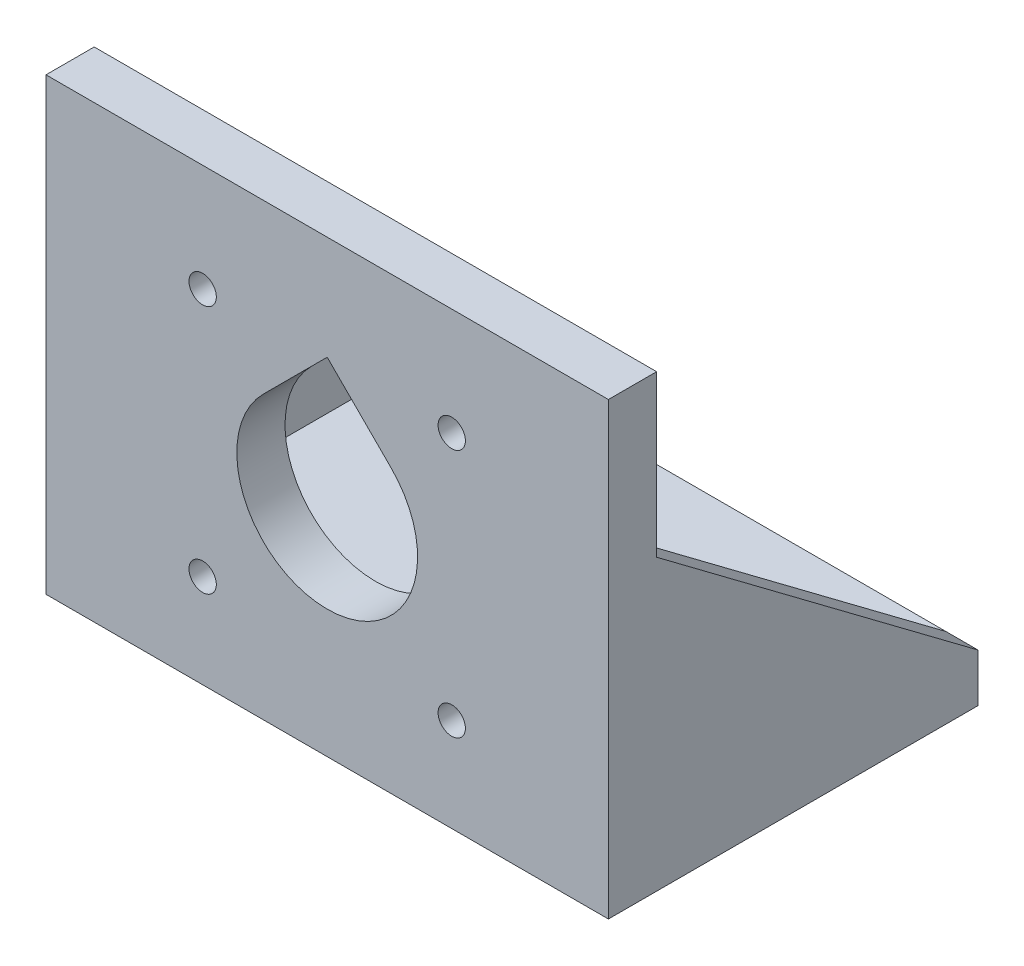
SolidWorks part; units mm, degrees
ref_plane "Спереди" through (0, 0, 0) normal (0, 0, 1) x (1, 0, 0)
ref_plane "Сверху" through (0, 0, 0) normal (0, 1, 0) x (1, 0, 0)
ref_plane "Справа" through (0, 0, 0) normal (1, 0, 0) x (0, 0, -1)
other "Configuration Table"
sketch "01_Пластина_эскиз" plane through (0, 0, 0) normal (0, 0, 1) x (1, 0, 0)
  line L1 (0, 0) -> (70, 0)
  line L2 (0, 0) -> (0, 56)
  line L3 (0, 56) -> (70, 56)
  line L4 (70, 0) -> (70, 56)
  dimension "D1" = 70
  dimension "D2" = 56
extrude "01_Передняя_пластина" add sketch "01_Пластина_эскиз" along normal blind 6
sketch "02_Полка_эскиз" plane through (0, 0, 0) normal (0, 1, 0) x (1, 0, 0)
  line L1 (0, 40) -> (70, 40)
  line L2 (0, 40) -> (0, -6)
  line L3 (0, -6) -> (70, -6)
  line L4 (70, 40) -> (70, -6)
  dimension "D1" = 70
  dimension "D2" = 46
  dimension "D3" = 6
  dimension "D4" = 6
extrude "02_Полка" add sketch "02_Полка_эскиз" along normal blind 6
sketch "03_Косынка_левая_эскиз" plane through (0, 0, 0) normal (1, 0, 0) x (0, 0, -1)
  line L0 (40, 6) -> (0, 6)
  line L1 (0, 6) -> (0, 36)
  line L2 (0, 36) -> (40, 6)
  dimension "D3" = 6
  dimension "D1" = 40
  dimension "D2" = 30
extrude "03_Косынка_левая" add sketch "03_Косынка_левая_эскиз" along normal blind 4
sketch "04_Косынка_правая_эскиз" plane through (0, 0, 0) normal (1, 0, 0) x (0, 0, -1)
  line L0 (40, 6) -> (0, 6)
  line L1 (0, 6) -> (0, 36)
  line L2 (0, 36) -> (40, 6)
  dimension "D3" = 6
  dimension "D1" = 40
  dimension "D2" = 30
extrude "04_Косынка_правая" add sketch "04_Косынка_правая_эскиз" along normal blind 4 from offset 66
sketch "05_Мотор_передний_фланец_эскиз" plane through (0, 0, 0) normal (0, 0, 1) x (1, 0, 0)
  line L0 (4, 6) -> (66, 6) construction
  circle A0 centre (35, 27.15) radius 11.25
  circle A1 centre (19.5, 11.65) radius 1.7
  circle A2 centre (19.5, 42.65) radius 1.7
  circle A3 centre (50.5, 11.65) radius 1.7
  circle A4 centre (50.5, 42.65) radius 1.7
  dimension "D1" = 3.4
  dimension "D2" = 3.4
  dimension "D3" = 3.4
  dimension "D4" = 3.4
  dimension "D5" = 22.5
  dimension "D6" = 15.5
  dimension "D7" = 31
  dimension "D8" = 15.5
  dimension "D9" = 31
  dimension "D10" = 35
  dimension "D11" = 21.15
extrude "05_Буртик_и_4_отверстия_М3" cut sketch "05_Мотор_передний_фланец_эскиз" against normal through all and the other way through all
sketch "06_Свод_45град_эскиз" plane through (0, 0, 0) normal (0, 0, 1) x (1, 0, 0)
  line L0 (27.045, 35.105) -> (42.955, 35.105)
  line L1 (42.955, 35.105) -> (35, 43.0599)
  line L2 (35, 43.0599) -> (27.045, 35.105)
  circle A0 centre (35, 27.15) radius 11.25 construction
  dimension "D1" = 7.955
  dimension "D2" = 15.9099
  dimension "D3" = 7.955
  dimension "D4" = 35
extrude "06_Свод_отверстия_для_печати" cut sketch "06_Свод_45град_эскиз" against normal through all and the other way through all
sketch "07_Крепление_полки_эскиз" plane through (0, 0, 0) normal (0, 1, 0) x (1, 0, 0)
  circle A0 centre (8.5, 12) radius 2.25
  circle A1 centre (8.5, 30) radius 2.25
  circle A2 centre (61.5, 12) radius 2.25
  circle A3 centre (61.5, 30) radius 2.25
  dimension "D1" = 4.5
  dimension "D2" = 4.5
  dimension "D3" = 4.5
  dimension "D4" = 4.5
  dimension "D5" = 53
  dimension "D6" = 18
  dimension "D7" = 8.5
  dimension "D8" = 12
extrude "07_4_отверстия_М4" cut sketch "07_Крепление_полки_эскиз" against normal through all and the other way through all
equation "\"Ширина\"= 70"
equation "\"Высота пластины\"= 56"
equation "\"Толщина стенок\"= 6"
equation "\"Длина полки\"= 40"
equation "\"Толщина косынки\"= 4"
equation "\"Высота косынки\"= 30"
equation "\"Высота оси\"= 30"
equation "\"Шаг М3 ПРЕДВ\"= 31"
equation "\"Отверстие буртика\"= 22.5"
equation "\"Отверстия М3\"= 3.4"
equation "\"Отверстия М4\"= 4.5"
equation "\"Отступ М4 сбоку\"= 8.5"
equation "\"Ближний ряд М4\"= 12"
equation "\"Отступ М4 сзади\"= 10"
equation "\"D1@01_Пластина_эскиз\" = \"Ширина\""
equation "\"D2@01_Пластина_эскиз\" = \"Высота пластины\""
equation "\"D1@01_Передняя_пластина\" = \"Толщина стенок\""
equation "\"D1@02_Полка_эскиз\" = \"Ширина\""
equation "\"D2@02_Полка_эскиз\" = \"Длина полки\" + \"Толщина стенок\""
equation "\"D1@02_Полка\" = \"Толщина стенок\""
equation "\"D1@03_Косынка_левая_эскиз\" = \"Длина полки\""
equation "\"D2@03_Косынка_левая_эскиз\" = \"Высота косынки\""
equation "\"D1@03_Косынка_левая\" = \"Толщина косынки\""
equation "\"D1@04_Косынка_правая_эскиз\" = \"Длина полки\""
equation "\"D2@04_Косынка_правая_эскиз\" = \"Высота косынки\""
equation "\"D1@04_Косынка_правая\" = \"Толщина косынки\""
equation "\"D19@04_Косынка_правая\" = \"Ширина\" - \"Толщина косынки\""
equation "\"D1@05_Мотор_передний_фланец_эскиз\" = \"Отверстия М3\""
equation "\"D2@05_Мотор_передний_фланец_эскиз\" = \"Отверстия М3\""
equation "\"D3@05_Мотор_передний_фланец_эскиз\" = \"Отверстия М3\""
equation "\"D4@05_Мотор_передний_фланец_эскиз\" = \"Отверстия М3\""
equation "\"D5@05_Мотор_передний_фланец_эскиз\" = \"Отверстие буртика\""
equation "\"D6@05_Мотор_передний_фланец_эскиз\" = \"Шаг М3 ПРЕДВ\" / 2"
equation "\"D7@05_Мотор_передний_фланец_эскиз\" = \"Шаг М3 ПРЕДВ\""
equation "\"D8@05_Мотор_передний_фланец_эскиз\" = \"Шаг М3 ПРЕДВ\" / 2"
equation "\"D9@05_Мотор_передний_фланец_эскиз\" = \"Шаг М3 ПРЕДВ\""
equation "\"D1@07_Крепление_полки_эскиз\" = \"Отверстия М4\""
equation "\"D2@07_Крепление_полки_эскиз\" = \"Отверстия М4\""
equation "\"D3@07_Крепление_полки_эскиз\" = \"Отверстия М4\""
equation "\"D4@07_Крепление_полки_эскиз\" = \"Отверстия М4\""
equation "\"D5@07_Крепление_полки_эскиз\" = \"Ширина\" - 2 * \"Отступ М4 сбоку\""
equation "\"D3@02_Полка_эскиз\" = \"Толщина стенок\""
equation "\"D3@03_Косынка_левая_эскиз\" = \"Толщина стенок\""
equation "\"D3@04_Косынка_правая_эскиз\" = \"Толщина стенок\""
equation "\"D10@05_Мотор_передний_фланец_эскиз\" = \"Ширина\" / 2"
equation "\"D1@06_Свод_45град_эскиз\" = \"Отверстие буртика\" / (2 * SQR(2))"
equation "\"D2@06_Свод_45град_эскиз\" = \"Отверстие буртика\" / SQR(2)"
equation "\"D3@06_Свод_45град_эскиз\" = \"Отверстие буртика\" / (2 * SQR(2))"
equation "\"D4@06_Свод_45град_эскиз\" = \"Ширина\" / 2"
equation "\"D6@07_Крепление_полки_эскиз\" = \"Длина полки\" - \"Ближний ряд М4\" - \"Отступ М4 сзади\""
equation "\"D7@07_Крепление_полки_эскиз\" = \"Отступ М4 сбоку\""
equation "\"D8@07_Крепление_полки_эскиз\" = \"Ближний ряд М4\""
